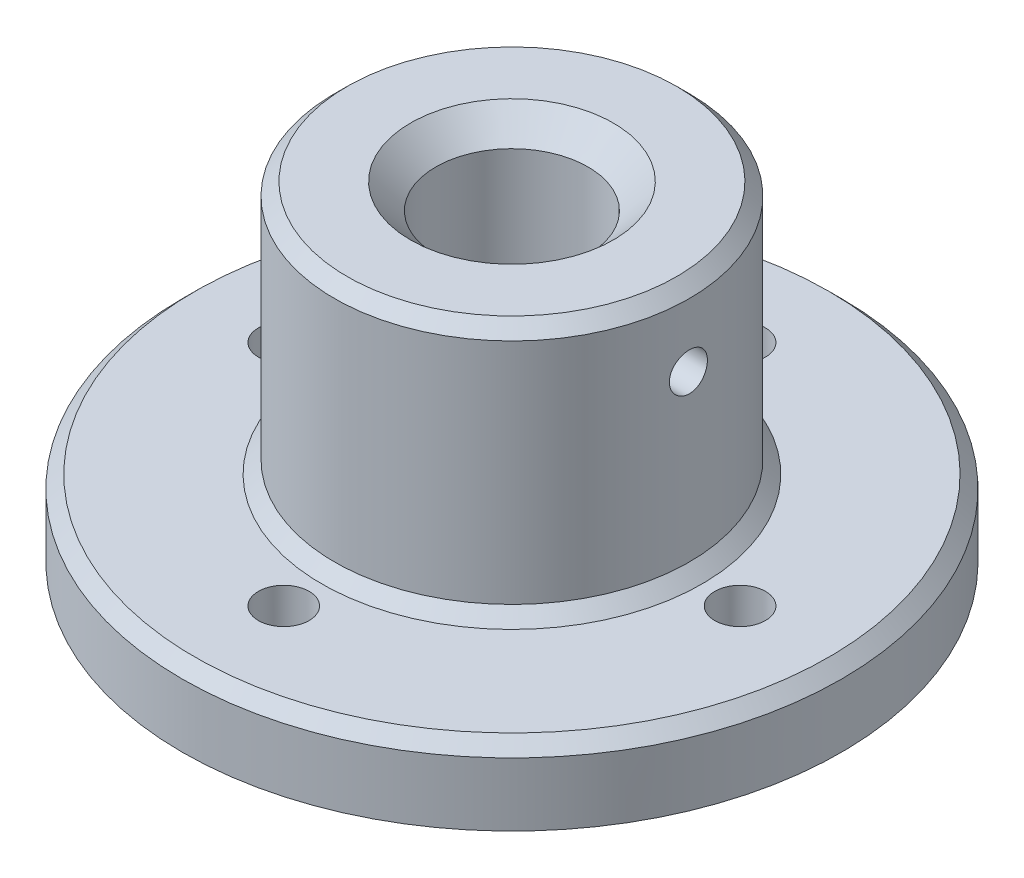
SolidWorks part; units mm, degrees
material "Manganese Bronze"
ref_plane "Front Plane" through (0, 0, 0) normal (0, 0, 1) x (1, 0, 0)
ref_plane "Top Plane" through (0, 0, 0) normal (0, 1, 0) x (1, 0, 0)
ref_plane "Right Plane" through (0, 0, 0) normal (1, 0, 0) x (0, 0, -1)
sketch "Sketch1" plane through (0, 0, 0) normal (0, 0, 1) x (1, 0, 0)
  line L0 (34.925, 0) -> (34.925, 3.175)
  line L1 (55, 0) -> (-55, 0) construction
  line L2 (34.925, 3.175) -> (12.7, 3.175)
  line L3 (12.7, 3.175) -> (12.7, 12.7)
  line L4 (12.7, 12.7) -> (9.525, 12.7)
  line L5 (9.525, 12.7) -> (9.525, 41.275)
  line L6 (9.525, 41.275) -> (22.225, 41.275)
  line L7 (22.225, 41.275) -> (22.225, 9.525)
  line L8 (22.225, 9.525) -> (41.275, 9.525)
  line L9 (41.275, 9.525) -> (41.275, 0)
  line L10 (41.275, 0) -> (34.925, 0)
  line L11 (0, -55) -> (0, 55) construction
  line L12 (0, 48.3611) -> (0, -30.2672) construction
  dimension "D1" = 9.525
  dimension "D2" = 22.225
  dimension "D3" = 41.275
  dimension "D4" = 12.7
  dimension "D5" = 12.7
  dimension "D6" = 34.925
  dimension "D7" = 41.275
  dimension "D8" = 3.175
  dimension "D9" = 9.525
revolve "Revolve1" add sketch "Sketch1" angle 360 about L12
chamfer "Chamfer1" distance 3.175 angle 45 1 edges at (0, 41.275, 9.525)
chamfer "Chamfer2" distance 1.5875 angle 45 3 edges at (0, 9.525, 41.275) (0, 9.525, 22.225) (0, 41.275, 22.225)
sketch "Sketch2" plane through (0, 41.275, 0) normal (0, 1, 0) x (1, 0, 0)
  line L0 (0, 0) -> (28.575, 0)
  circle A0 centre (0, 0) radius 28.575 construction
  circle A1 centre (28.575, 0) radius 3.175
  point P5 (0, 0)
  dimension "D1" = 57.15
  dimension "D2" = 6.35
extrude "Cut-Extrude2" cut sketch "Sketch2" against normal through all
pattern_circular "CirPattern2" count 4 over 360 about axis through (0, 0, 0) along (0, 1, 0) of "Cut-Extrude2"
sketch "Sketch3" plane through (0, 0, 0) normal (1, 0, 0) x (0, 0, -1)
  line L0 (0, 22.7012) -> (0, -22.7012) construction
  line L1 (45.4025, 0) -> (-45.4025, 0) construction
  circle A0 centre (0, 31.75) radius 2.3812
  point P6 (0, 0)
  dimension "D2" = 4.7625
  dimension "D1" = 31.75
extrude "Cut-Extrude3" cut sketch "Sketch3" along normal through all
